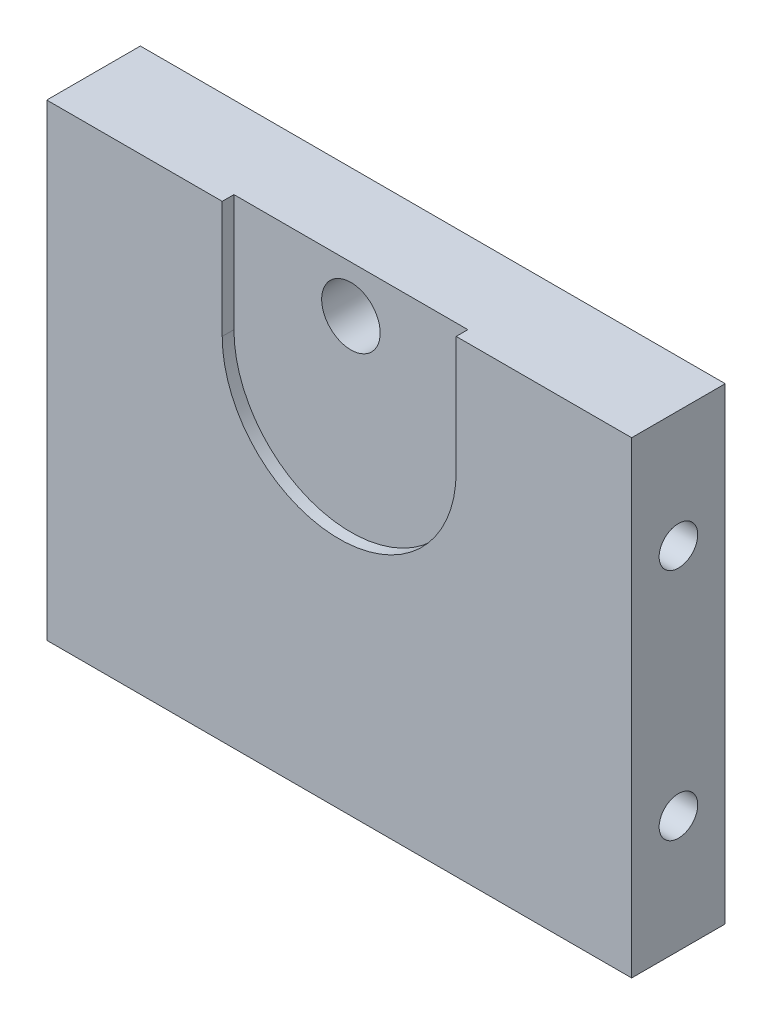
SolidWorks part; units mm, degrees
material "6061 Сплав"
ref_plane "Front" through (0, 0, 0) normal (0, 0, 1) x (1, 0, 0)
ref_plane "Top" through (0, 0, 0) normal (0, 1, 0) x (1, 0, 0)
ref_plane "Right" through (0, 0, 0) normal (1, 0, 0) x (0, 0, -1)
sketch "Эскиз1" plane through (0, 0, 0) normal (0, 0, 1) x (1, 0, 0)
  line L1 (-25, 20) -> (25, 20)
  line L2 (-25, 20) -> (-25, -20)
  line L3 (-25, -20) -> (25, -20)
  line L4 (25, 20) -> (25, -20)
  line L5 (-25, 20) -> (25, -20) construction
  line L6 (-25, -20) -> (25, 20) construction
  point P0 (0, 0)
  dimension "D1" = 50
  dimension "D2" = 40
extrude "Бобышка-Вытянуть1" add sketch "Эскиз1" along normal blind 8
sketch "Эскиз2" plane through (25, 0, 0) normal (1, 0, 0) x (0, 0, -1)
  line L0 (0, -20) -> (0, 20) construction
  line L1 (-8, -20) -> (0, -20) construction
  line L2 (-8, 20) -> (0, 20) construction
  circle A0 centre (-4, 10) radius 1.65
  circle A1 centre (-4, -10) radius 1.65
  dimension "D1" = 4
  dimension "D2" = 4
  dimension "D3" = 10
  dimension "D4" = 10
extrude "Вырез-Вытянуть1" cut sketch "Эскиз2" against normal blind 15
sketch "Эскиз4" plane through (0, 0, 8) normal (0, 0, 1) x (1, 0, 0)
  line L0 (-10, 20) -> (10, 20)
  line L1 (25, 20) -> (-25, 20) construction
  line L2 (10, 20) -> (10, 10)
  line L3 (-10, 20) -> (-10, 10)
  line L4 (-25, 20) -> (-25, -20) construction
  arc A0 (-10, 10) -> (10, 10) centre (0, 10) ccw
  dimension "D1" = 20
  dimension "D2" = 15
  dimension "D3" = 10
extrude "Вырез-Вытянуть2" cut sketch "Эскиз4" against normal blind 1
sketch "Эскиз5" plane through (0, 0, 7) normal (0, 0, 1) x (1, 0, 0)
  line L0 (10, 20) -> (-10, 20) construction
  line L1 (25, -20) -> (25, 20) construction
  circle A0 centre (0, 16) radius 2.5
  dimension "D1" = 4
  dimension "D2" = 25
extrude "Вырез-Вытянуть3" cut sketch "Эскиз5" against normal blind 10
